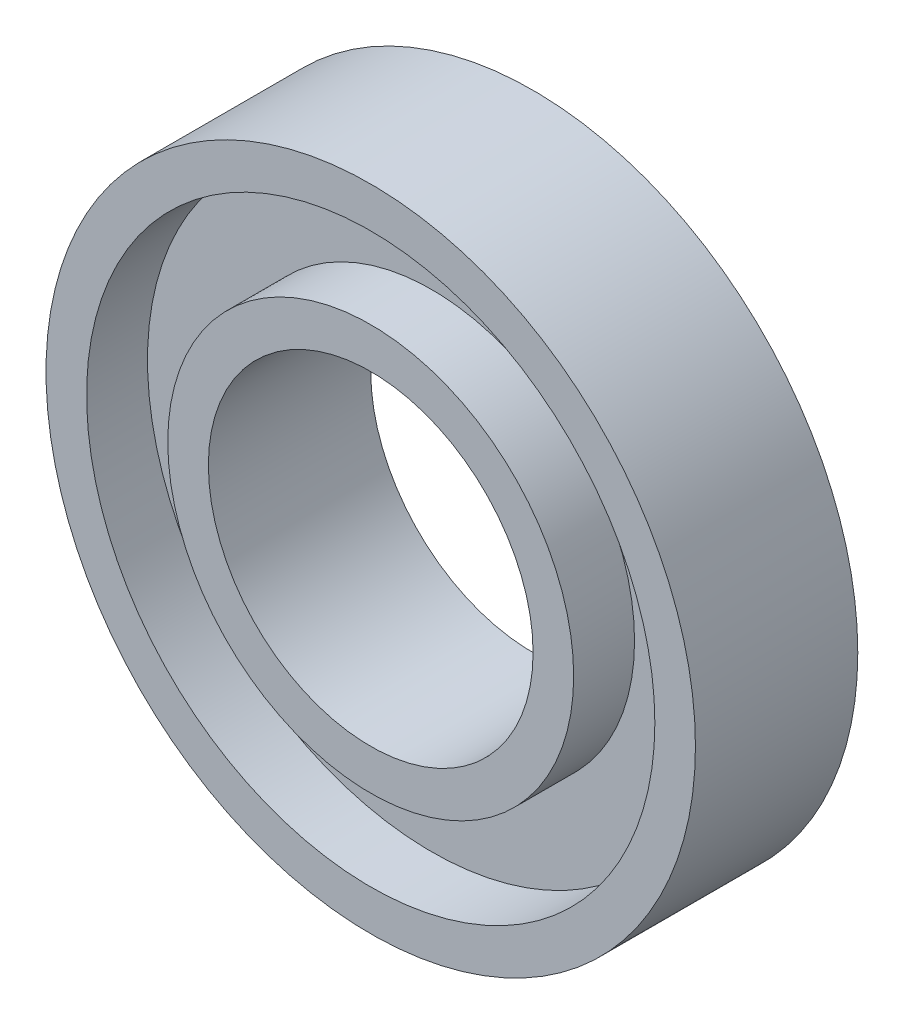
SolidWorks part; units mm, degrees
ref_plane "前视基准面" through (0, 0, 0) normal (0, 0, 1) x (1, 0, 0)
ref_plane "上视基准面" through (0, 0, 0) normal (0, 1, 0) x (1, 0, 0)
ref_plane "右视基准面" through (0, 0, 0) normal (1, 0, 0) x (0, 0, -1)
sketch "草图1" plane through (0, 0, 0) normal (0, 0, 1) x (1, 0, 0)
  circle A0 centre (0, 0) radius 4
  circle A1 centre (0, 0) radius 8
  dimension "D1" = 8
  dimension "D2" = 16
extrude "凸台-拉伸1" add sketch "草图1" along normal blind 4
ref_plane "基准面1" through (0, 0, 2) normal (0, 0, 1) x (1, 0, 0)
sketch "草图2" plane through (0, 0, 4) normal (0, 0, 1) x (1, 0, 0)
  circle A0 centre (0, 0) radius 5
  circle A1 centre (0, 0) radius 7
  dimension "D1" = 10
  dimension "D2" = 14
extrude "切除-拉伸1" cut sketch "草图2" against normal blind 1.5
mirror "镜向1" about plane through (0, 0, 2) normal (0, 0, 1) of "切除-拉伸1"
